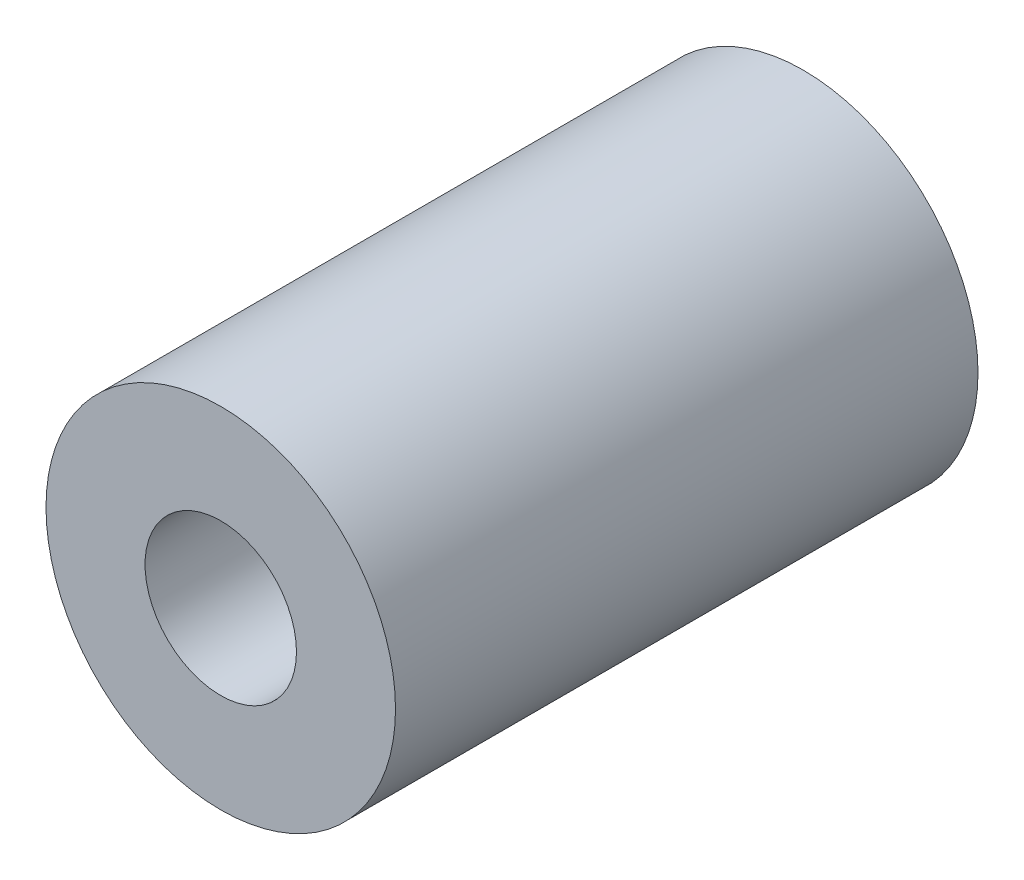
SolidWorks part; units mm, degrees
ref_plane "正面" through (0, 0, 0) normal (0, 0, 1) x (1, 0, 0)
ref_plane "平面" through (0, 0, 0) normal (0, 1, 0) x (1, 0, 0)
ref_plane "右側面" through (0, 0, 0) normal (1, 0, 0) x (0, 0, -1)
sketch "ｽｹｯﾁ1" plane through (0, 0, 0) normal (0, 0, 1) x (1, 0, 0)
  circle A0 centre (0, 0) radius 3
  circle A1 centre (0, 0) radius 1.3
  dimension "D1" = 6
  dimension "D2" = 2.6
extrude "ﾎﾞｽ - 押し出し1" add sketch "ｽｹｯﾁ1" along normal blind 10
